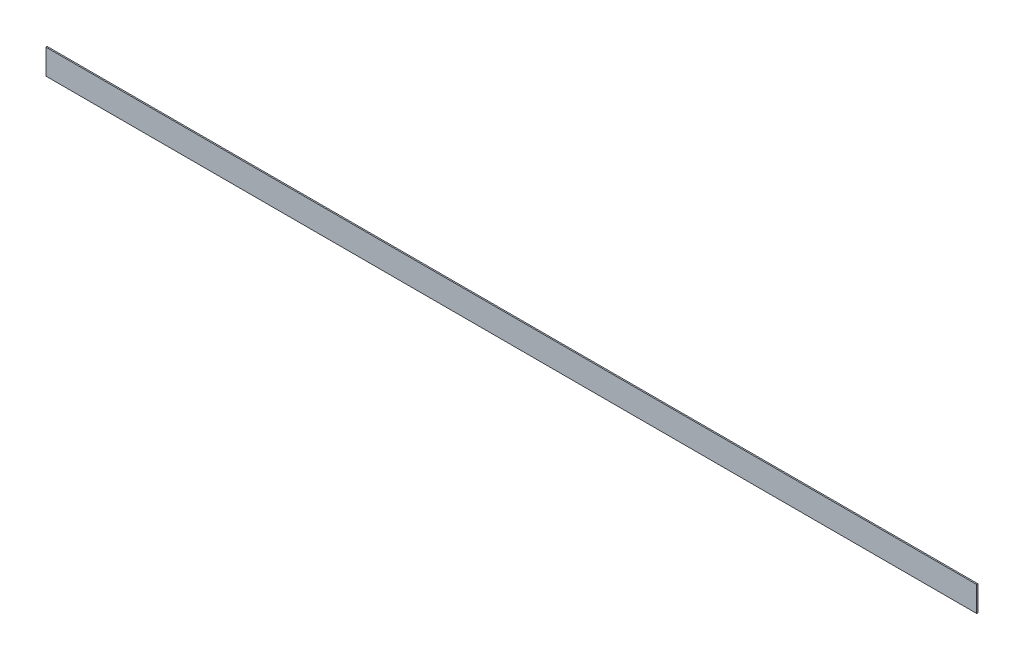
SolidWorks part; units mm, degrees
ref_plane "Front Plane" through (0, 0, 0) normal (0, 0, 1) x (1, 0, 0)
ref_plane "Top Plane" through (0, 0, 0) normal (0, 1, 0) x (1, 0, 0)
ref_plane "Right Plane" through (0, 0, 0) normal (1, 0, 0) x (0, 0, -1)
sketch "Sketch2" plane through (0, 0, 0) normal (0, 0, 1) x (1, 0, 0)
  line L1 (370, -10) -> (-370, -10)
  line L2 (370, -10) -> (370, 10)
  line L3 (370, 10) -> (-370, 10)
  line L4 (-370, -10) -> (-370, 10)
  line L5 (370, -10) -> (-370, 10) construction
  line L6 (370, 10) -> (-370, -10) construction
  point P0 (0, 0)
  dimension "D1" = 740
  dimension "D2" = 20
extrude "Boss-Extrude1" add sketch "Sketch2" along normal blind 1
